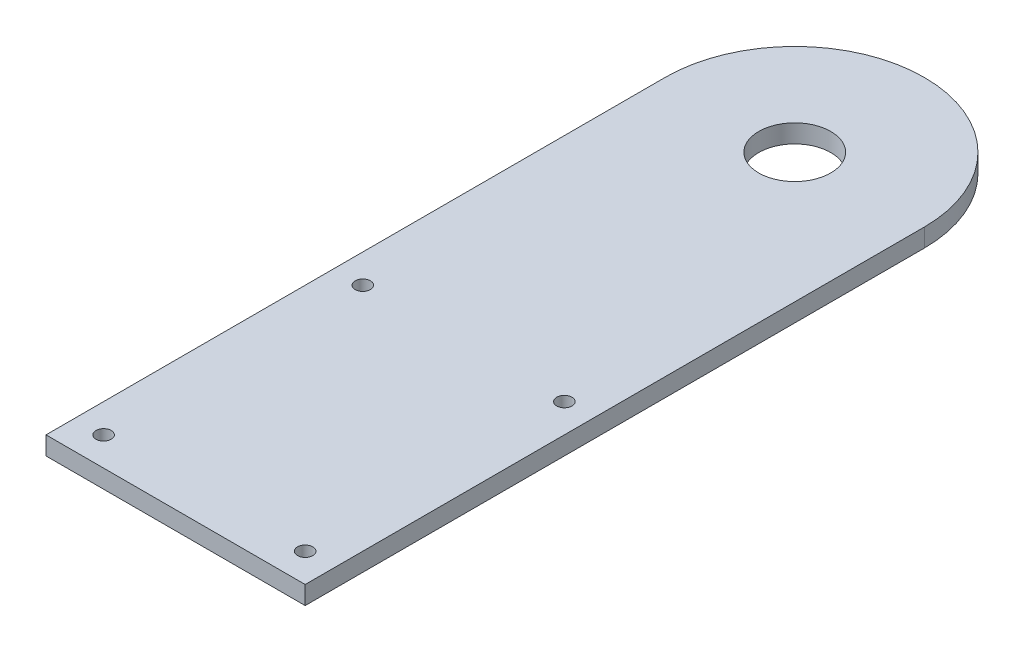
SolidWorks part; units mm, degrees
material "6061 Alloy"
ref_plane "Front Plane" through (0, 0, 0) normal (0, 0, 1) x (1, 0, 0)
ref_plane "Top Plane" through (0, 0, 0) normal (0, 1, 0) x (1, 0, 0)
ref_plane "Right Plane" through (0, 0, 0) normal (1, 0, 0) x (0, 0, -1)
sketch "Sketch1" plane through (0, 0, 0) normal (0, 1, 0) x (1, 0, 0)
  line L0 (-45, -107.5) -> (-45, 107.5)
  line L1 (-45, -107.5) -> (45, -107.5)
  line L2 (45, -107.5) -> (45, 107.5)
  line L4 (-35, -7.5) -> (35, -7.5) construction
  line L5 (-35, -7.5) -> (-35, -97.5) construction
  line L6 (-35, -97.5) -> (35, -97.5) construction
  line L7 (35, -7.5) -> (35, -97.5) construction
  arc A0 (-45, 107.5) -> (45, 107.5) centre (0, 107.5) cw
  circle A1 centre (-35, -7.5) radius 2.5 construction
  circle A2 centre (35, -7.5) radius 2.5 construction
  circle A3 centre (35, -97.5) radius 2.5 construction
  circle A4 centre (-35, -97.5) radius 2.5 construction
  circle A5 centre (0, 107.5) radius 12.5
  point P5 (0, -97.5)
  point P7 (0, -107.5)
  point P8 (45, 0)
  dimension "D3" = 5
  dimension "D7" = 25
  dimension "D1" = 70
  dimension "D2" = 90
  dimension "D4" = 10
  dimension "D5" = 90
  dimension "D6" = 215
extrude "Boss-Extrude1" add sketch "Sketch1" against normal blind 6.35 contours L0 A0 L2 L1
hole_wizard "M5 Clearance Hole1" positions "3DSketch1" profile "Sketch2" hole size "M5" standard "ANSI Metric" end condition through all
sketch3d "3DSketch1"
  point P0 (-35, 0, 7.5)
  point P2 (35, 0, 7.5)
  point P4 (-35, 0, 97.5)
  point P6 (35, 0, 97.5)
  point P9 (-35, 0, -30)
  point P11 (35, 0, -30)
  point P13 (35, 0, 60)
  point P15 (-35, 0, 60)
sketch "Sketch2" plane through (-35, 0, 7.5) normal (1, 0, 0) x (0, 0, 1)
  line L0 (0, 0) -> (0, 6.35)
  line L1 (0, 6.35) -> (2.65, 6.35)
  line L2 (2.65, 6.35) -> (2.65, 0)
  line L5 (2.65, 0) -> (0, 0)
  line L11 (0, -6.35) -> (0, 107.95) construction
  dimension "Thru Hole Dia." = 5.3
  dimension "Thru Hole Depth" = 6.35
